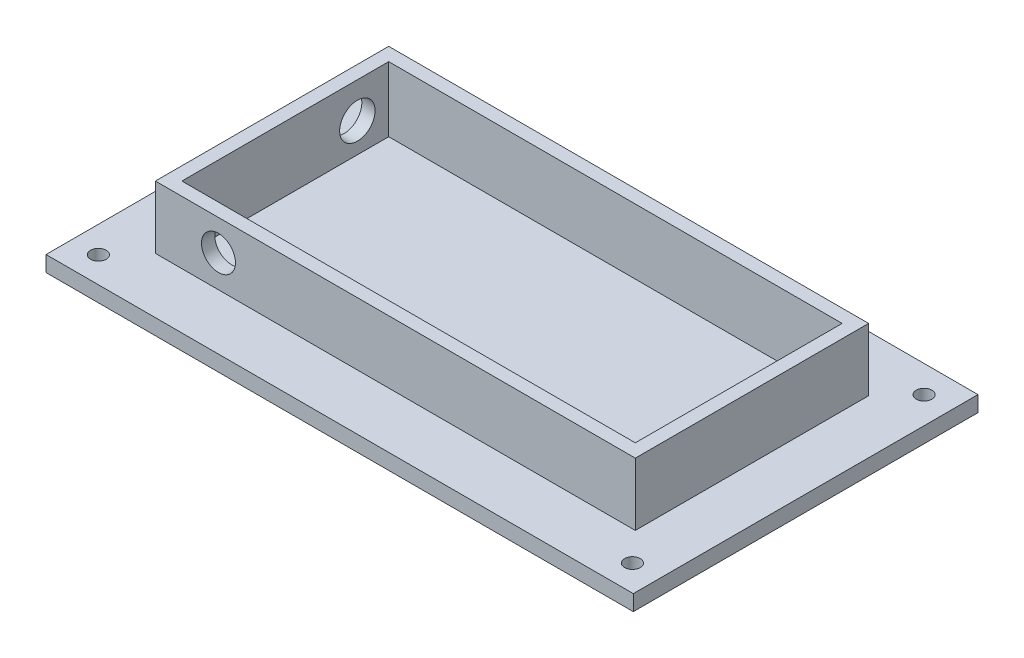
SolidWorks part; units mm, degrees
ref_plane "Front Plane" through (0, 0, 0) normal (0, 0, 1) x (1, 0, 0)
ref_plane "Top Plane" through (0, 0, 0) normal (0, 1, 0) x (1, 0, 0)
ref_plane "Right Plane" through (0, 0, 0) normal (1, 0, 0) x (0, 0, -1)
sketch "Sketch1" plane through (0, 0, 0) normal (0, 1, 0) x (1, 0, 0)
  line L1 (-51.269, 25.9043) -> (61.253, 25.9043)
  line L2 (-51.269, 25.9043) -> (-51.269, -40.1357)
  line L3 (-51.269, -40.1357) -> (61.253, -40.1357)
  line L4 (61.253, 25.9043) -> (61.253, -40.1357)
  circle A0 centre (-46.2077, 20.7265) radius 1.5
  circle A1 centre (56.1004, 20.7265) radius 1.5
  circle A2 centre (56.1004, -35.1559) radius 1.5
  circle A3 centre (-46.2077, -35.1559) radius 1.5
  dimension "D3" = 3
  dimension "D4" = 3
  dimension "D5" = 3
  dimension "D6" = 3
  dimension "D1" = 112.522
  dimension "D2" = 66.04
extrude "Boss-Extrude1" add sketch "Sketch1" along normal blind 3
sketch "Sketch4" plane through (0, 3, 0) normal (0, 1, 0) x (1, 0, 0)
  line L1 (-40.982, 15.2363) -> (50.966, 15.2363)
  line L2 (-40.982, 15.2363) -> (-40.982, -29.4677)
  line L3 (-40.982, -29.4677) -> (50.966, -29.4677)
  line L4 (50.966, 15.2363) -> (50.966, -29.4677)
  line L5 (-51.269, 25.9043) -> (-51.269, -40.1357) construction
  line L6 (61.253, -40.1357) -> (61.253, 25.9043) construction
  line L7 (61.253, 25.9043) -> (-51.269, 25.9043) construction
  line L8 (-51.269, -40.1357) -> (61.253, -40.1357) construction
  dimension "D1" = 10.287
  dimension "D2" = 10.287
  dimension "D3" = 10.668
  dimension "D4" = 10.668
extrude "Boss-Extrude2" add sketch "Sketch4" along normal blind 12 contours L1 L4 L3 L2
shell "Shell1" thickness 2.54
sketch "Sketch13" plane through (0, 0, 29.4677) normal (0, 0, 1) x (1, 0, 0)
  circle A0 centre (-28.8928, 9.1185) radius 3.2534
extrude "Cut-Extrude1" cut sketch "Sketch13" against normal blind 8.19
sketch "Sketch15" plane through (-40.982, 0, 0) normal (-1, 0, 0) x (0, 0, 1)
  circle A0 centre (-6.6934, 8.1974) radius 3.3938
extrude "Cut-Extrude2" cut sketch "Sketch15" against normal blind 8.19
scale "Scale1" scale about centroid uniform scaling yes scale factor 1.5
ref_plane "Plane7" through (-64.0915, 20.7509, -26.4032) normal (1, 0, 0) x (0, 0, -1)
